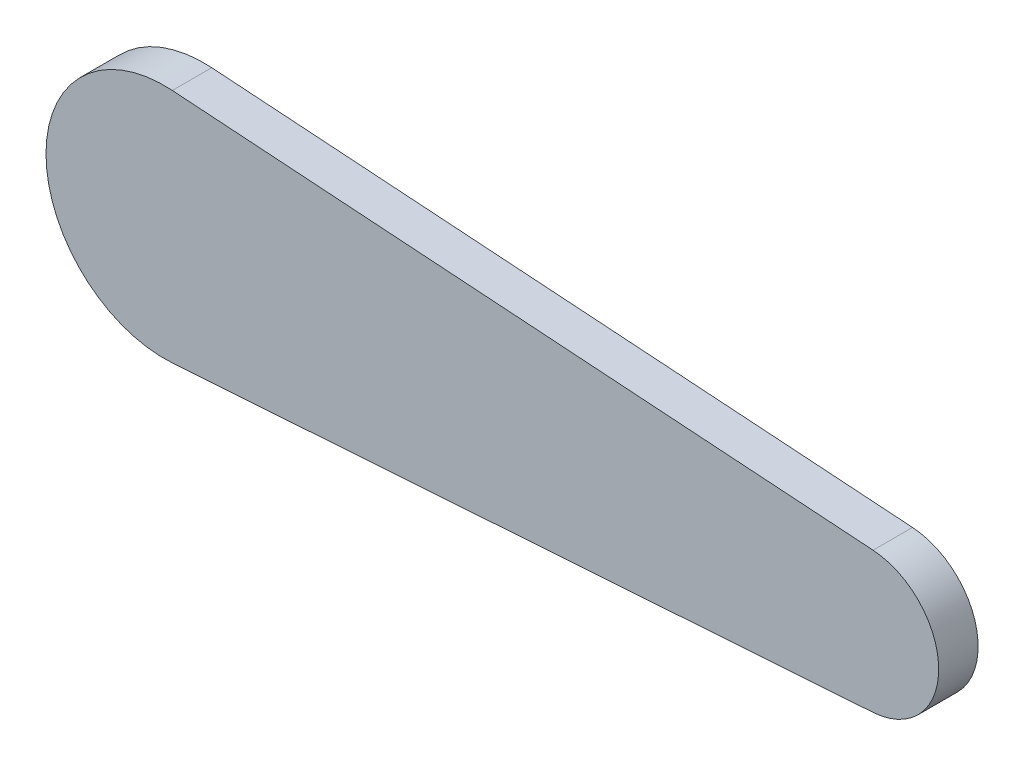
SolidWorks part; units mm, degrees
ref_plane "前视基准面" through (0, 0, 0) normal (0, 0, 1) x (1, 0, 0)
ref_plane "上视基准面" through (0, 0, 0) normal (0, 1, 0) x (1, 0, 0)
ref_plane "右视基准面" through (0, 0, 0) normal (1, 0, 0) x (0, 0, -1)
other "Configuration Table"
sketch "草图2" plane through (0, 0, 0) normal (0, 0, 1) x (1, 0, 0)
  line L0 (0, 0) -> (125, 0) construction
  line L1 (1.428, 20.9514) -> (125.85, 12.4711)
  line L2 (1.428, -20.9514) -> (125.85, -12.4711)
  arc A0 (1.428, 20.9514) -> (1.428, -20.9514) centre (0, 0) ccw
  arc A1 (125.85, -12.4711) -> (125.85, 12.4711) centre (125, 0) ccw
  dimension "D2" = 21
  dimension "D3" = 25
  dimension "D1" = 125
extrude "凸台-拉伸1" add sketch "草图2" along normal blind 7
sketch "草图3" plane through (0, 0, 7) normal (0, 0, 1) x (1, 0, 0)
  circle A0 centre (0, 0) radius 21
  circle A1 centre (125, 0) radius 12.5037
